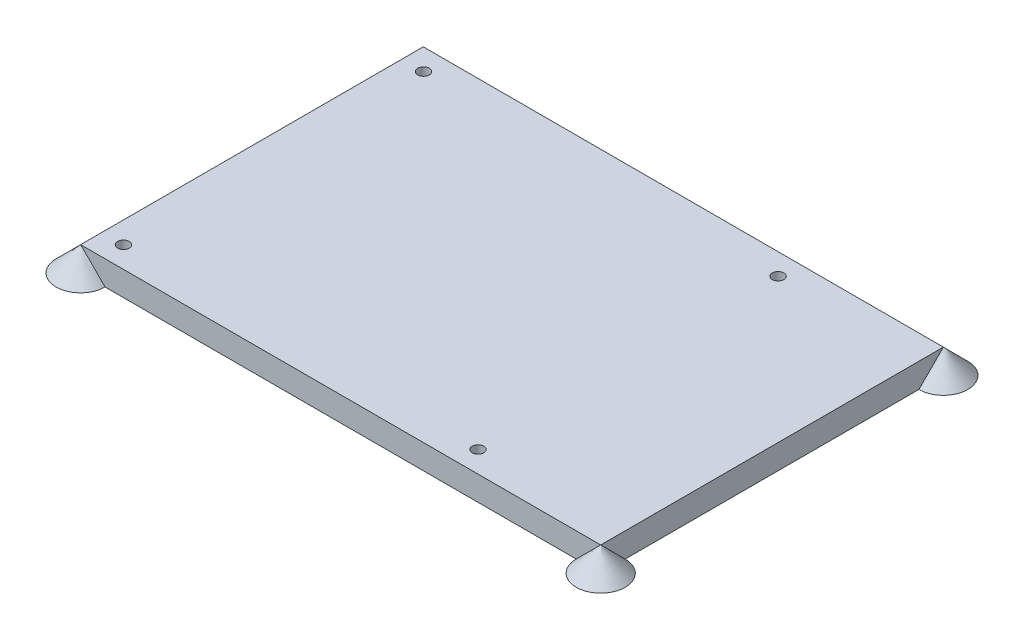
SolidWorks part; units mm, degrees
ref_plane "Front Plane" through (0, 0, 0) normal (0, 0, 1) x (1, 0, 0)
ref_plane "Top Plane" through (0, 0, 0) normal (0, 1, 0) x (1, 0, 0)
ref_plane "Right Plane" through (0, 0, 0) normal (1, 0, 0) x (0, 0, -1)
sketch "Sketch1" plane through (0, 0, 0) normal (0, 1, 0) x (1, 0, 0)
  line L0 (17.68, -24.52) -> (-37.7, -24.52) construction
  line L1 (-42.5, -28) -> (42.5, -28)
  line L2 (-42.5, -28) -> (-42.5, 28)
  line L3 (-42.5, 28) -> (42.5, 28)
  line L4 (42.5, -28) -> (42.5, 28)
  line L5 (-42.5, -28) -> (42.5, 28) construction
  line L6 (-42.5, 28) -> (42.5, -28) construction
  line L7 (-10.01, -24.52) -> (-10.01, -13.8269) construction
  line L8 (-46.75, 0) -> (46.75, 0) construction
  circle A0 centre (-38.98, -24.52) radius 1.28 construction
  circle A1 centre (18.96, -24.52) radius 1.28 construction
  circle A2 centre (-38.98, -24.52) radius 0.95
  circle A3 centre (18.96, -24.52) radius 0.95
  circle A4 centre (18.96, 24.52) radius 0.95
  circle A5 centre (-38.98, 24.52) radius 0.95
  point P0 (0, 0)
  dimension "D3" = 2.56
  dimension "D4" = 2.24
  dimension "D5" = 2.2
  dimension "D6" = 55.38
  dimension "D7" = 1.9
  dimension "D1" = 85
  dimension "D2" = 56
extrude "Boss-Extrude2" add sketch "Sketch1" along normal blind 4
sketch "Sketch5" plane through (0, 0, 0) normal (0, 1, 0) x (1, 0, 0)
  line L0 (-42.5, -28) -> (-45.3284, -30.8284)
  dimension "D1" = 4
ref_plane "Plane2" through (-7.25, 0, -7.25) normal (0.7071, 0, 0.7071) x (0.7071, 0, -0.7071)
sketch "Sketch6" plane through (-7.25, 0, -7.25) normal (0.7071, 0, 0.7071) x (0.7071, 0, -0.7071)
  line L0 (-49.851, 4) -> (-53.851, 0)
  line L1 (-53.851, 0) -> (-49.851, 0)
  line L2 (-49.851, 0) -> (-49.851, 4)
revolve "Revolve1" add sketch "Sketch6" angle 360 about L2
mirror "Mirror1" about plane through (0, 0, 0) normal (1, 0, 0) of "Revolve1" second plane through (0, 0, 0) second plane normal (0, 0, 1)
